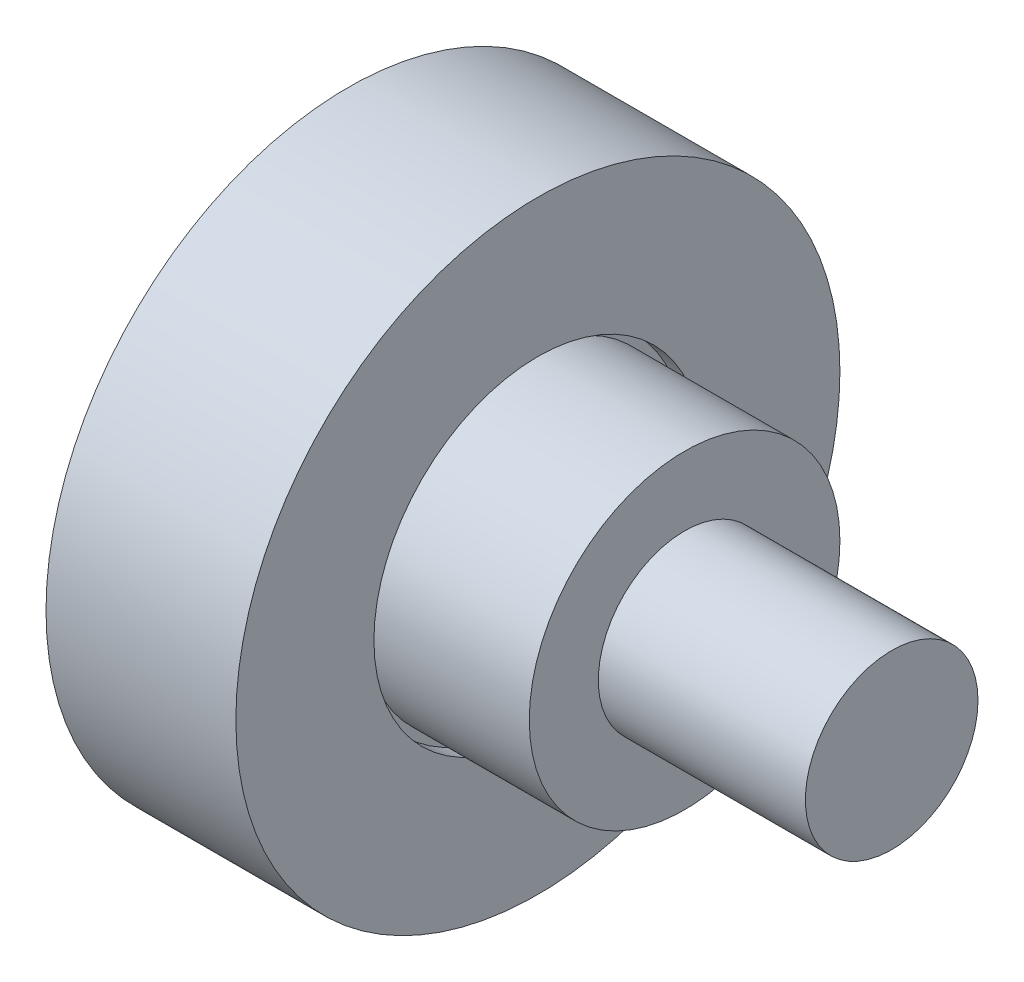
SolidWorks part; units mm, degrees
ref_plane "Front Plane" through (0, 0, 0) normal (0, 0, 1) x (1, 0, 0)
ref_plane "Top Plane" through (0, 0, 0) normal (0, 1, 0) x (1, 0, 0)
ref_plane "Right Plane" through (0, 0, 0) normal (1, 0, 0) x (0, 0, -1)
sketch "Sketch1" plane through (0, 0, 0) normal (1, 0, 0) x (0, 0, -1)
  circle A0 centre (0, 0) radius 35
  dimension "D1" = 70
extrude "Boss-Extrude1" add sketch "Sketch1" along normal blind 22
sketch "Sketch2" plane through (22, 0, 0) normal (1, 0, 0) x (0, 0, -1)
  circle A0 centre (0, 0) radius 18
  dimension "D1" = 36
extrude "Boss-Extrude2" add sketch "Sketch2" along normal blind 17
sketch "Sketch3" plane through (39, 0, 0) normal (1, 0, 0) x (0, 0, -1)
  circle A0 centre (0, 0) radius 10
  dimension "D1" = 20
extrude "Boss-Extrude3" add sketch "Sketch3" along normal blind 24
sketch "Sketch4" plane through (22, 0, 0) normal (1, 0, 0) x (0, 0, -1)
  circle A0 centre (0, 0) radius 18
  circle A1 centre (0, 0) radius 19
  dimension "D1" = 36
  dimension "D2" = 1
extrude "Cut-Extrude1" cut sketch "Sketch4" against normal blind 2
